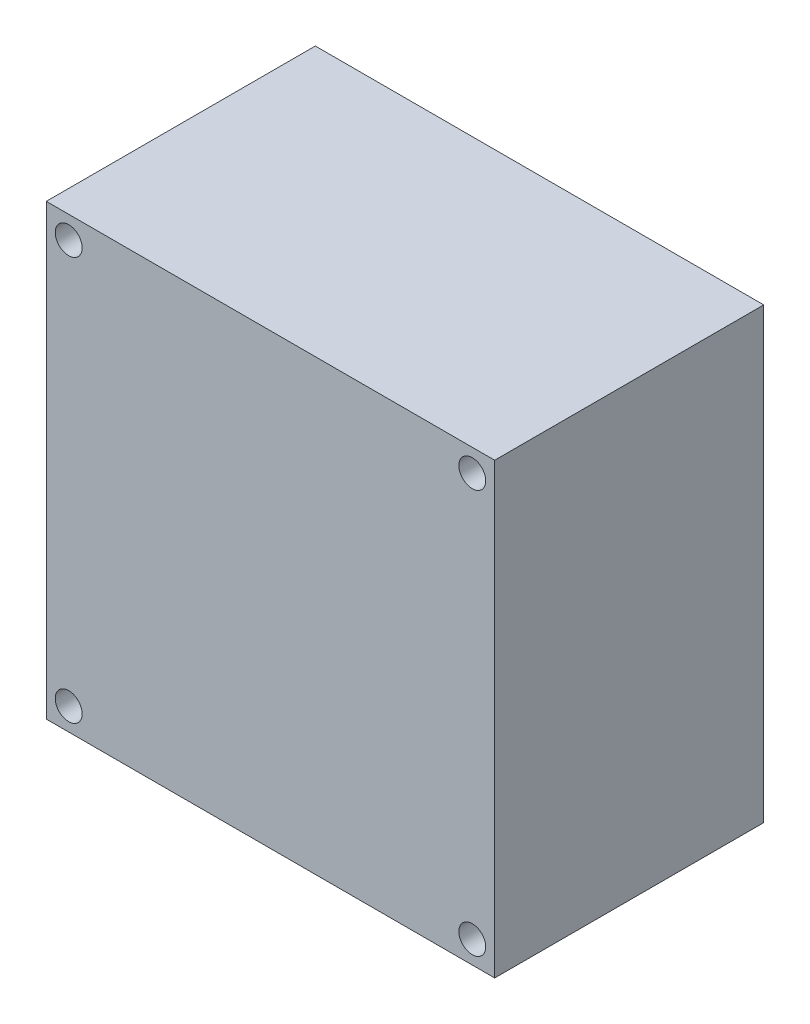
SolidWorks part; units mm, degrees
ref_plane "Plan de face" through (0, 0, 0) normal (0, 0, 1) x (1, 0, 0)
ref_plane "Plan de dessus" through (0, 0, 0) normal (0, 1, 0) x (1, 0, 0)
ref_plane "Plan de droite" through (0, 0, 0) normal (1, 0, 0) x (0, 0, -1)
sketch "Esquisse1" plane through (0, 0, 0) normal (0, 0, 1) x (1, 0, 0)
  line L1 (15.0118, 164.5995) -> (-34.9882, 164.5995)
  line L2 (15.0118, 164.5995) -> (15.0118, 214.5995)
  line L3 (15.0118, 214.5995) -> (-34.9882, 214.5995)
  line L4 (-34.9882, 164.5995) -> (-34.9882, 214.5995)
  circle A0 centre (12.5118, 167.0995) radius 1.5
  circle A1 centre (-32.4882, 167.0995) radius 1.5
  circle A2 centre (12.5118, 212.0995) radius 1.5
  circle A4 centre (-32.4882, 212.0995) radius 1.5
  dimension "D3" = 2.5
  dimension "D1" = 50
  dimension "D2" = 50
  dimension "D4" = 2.5
  dimension "D5" = 90
  dimension "D6" = 2
  dimension "D7" = 2
extrude "Boss.-Extru.1" add sketch "Esquisse1" along normal blind 30
